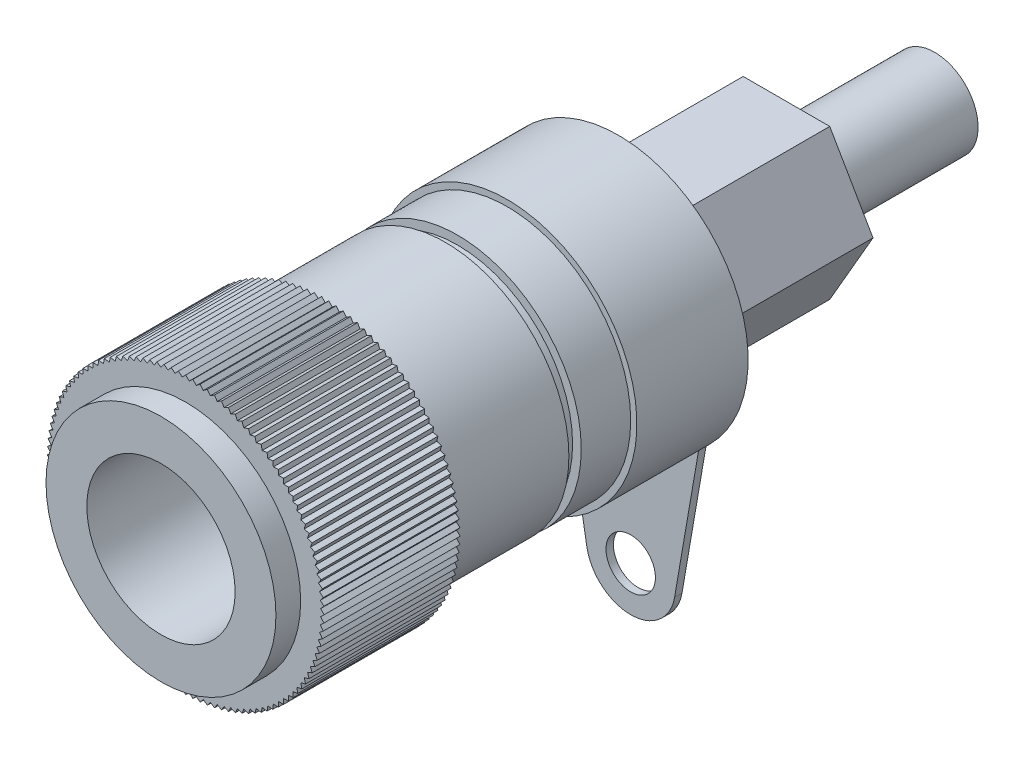
SolidWorks part; units mm, degrees
ref_plane "Alzado" through (0, 0, 0) normal (0, 0, 1) x (1, 0, 0)
ref_plane "Planta" through (0, 0, 0) normal (0, 1, 0) x (1, 0, 0)
ref_plane "Vista lateral" through (0, 0, 0) normal (1, 0, 0) x (0, 0, -1)
sketch "Croquis2" plane through (0, 0, 0) normal (0, 0, 1) x (1, 0, 0)
  circle A0 centre (0, 0) radius 3
  circle A1 centre (0, 0) radius 4.65
  dimension "D1" = 6
  dimension "D2" = 9.3
extrude "Saliente-Extruir1" add sketch "Croquis2" against normal blind 1
sketch "Croquis3" plane through (0, 0, -1) normal (0, 0, -1) x (-1, 0, 0)
  line L0 (0, 0) -> (0, 5.6) construction
  line L1 (0.1429, 5.4571) -> (0, 5.6)
  line L2 (0, 5.6) -> (-0.1429, 5.4571)
  line L3 (0.2931, 5.5923) -> (0.1429, 5.4571)
  line L4 (0.4283, 5.4421) -> (0.2931, 5.5923)
  line L5 (0.5854, 5.5693) -> (0.4283, 5.4421)
  line L6 (0.7125, 5.4123) -> (0.5854, 5.5693)
  line L7 (0.876, 5.5311) -> (0.7125, 5.4123)
  line L8 (0.9948, 5.3676) -> (0.876, 5.5311)
  line L9 (1.1643, 5.4776) -> (0.9948, 5.3676)
  line L10 (1.2744, 5.3081) -> (1.1643, 5.4776)
  line L11 (1.4494, 5.4092) -> (1.2744, 5.3081)
  line L12 (1.5504, 5.2342) -> (1.4494, 5.4092)
  line L13 (1.7305, 5.3259) -> (1.5504, 5.2342)
  line L14 (1.8222, 5.1459) -> (1.7305, 5.3259)
  line L15 (2.0069, 5.2281) -> (1.8222, 5.1459)
  line L16 (2.0891, 5.0434) -> (2.0069, 5.2281)
  line L17 (2.2777, 5.1159) -> (2.0891, 5.0434)
  line L18 (2.3501, 4.9272) -> (2.2777, 5.1159)
  line L19 (2.5423, 4.9896) -> (2.3501, 4.9272)
  line L20 (2.6048, 4.7974) -> (2.5423, 4.9896)
  line L21 (2.8, 4.8497) -> (2.6048, 4.7974)
  line L22 (2.8523, 4.6545) -> (2.8, 4.8497)
  line L23 (3.05, 4.6966) -> (2.8523, 4.6545)
  line L24 (3.092, 4.4989) -> (3.05, 4.6966)
  line L25 (3.2916, 4.5305) -> (3.092, 4.4989)
  line L26 (3.3232, 4.3309) -> (3.2916, 4.5305)
  line L27 (3.5242, 4.352) -> (3.3232, 4.3309)
  line L28 (3.5453, 4.151) -> (3.5242, 4.352)
  line L29 (3.7471, 4.1616) -> (3.5453, 4.151)
  line L30 (3.7577, 3.9598) -> (3.7471, 4.1616)
  line L31 (3.9598, 3.9598) -> (3.7577, 3.9598)
  line L32 (3.9598, 3.7577) -> (3.9598, 3.9598)
  line L33 (4.1616, 3.7471) -> (3.9598, 3.7577)
  line L34 (4.151, 3.5453) -> (4.1616, 3.7471)
  line L35 (4.352, 3.5242) -> (4.151, 3.5453)
  line L36 (4.3309, 3.3232) -> (4.352, 3.5242)
  line L37 (4.5305, 3.2916) -> (4.3309, 3.3232)
  line L38 (4.4989, 3.092) -> (4.5305, 3.2916)
  line L39 (4.6966, 3.05) -> (4.4989, 3.092)
  line L40 (4.6545, 2.8523) -> (4.6966, 3.05)
  line L41 (4.8497, 2.8) -> (4.6545, 2.8523)
  line L42 (4.7974, 2.6048) -> (4.8497, 2.8)
  line L43 (4.9896, 2.5423) -> (4.7974, 2.6048)
  line L44 (4.9272, 2.3501) -> (4.9896, 2.5423)
  line L45 (5.1159, 2.2777) -> (4.9272, 2.3501)
  line L46 (5.0434, 2.0891) -> (5.1159, 2.2777)
  line L47 (5.2281, 2.0069) -> (5.0434, 2.0891)
  line L48 (5.1459, 1.8222) -> (5.2281, 2.0069)
  line L49 (5.3259, 1.7305) -> (5.1459, 1.8222)
  line L50 (5.2342, 1.5504) -> (5.3259, 1.7305)
  line L51 (5.4092, 1.4494) -> (5.2342, 1.5504)
  line L52 (5.3081, 1.2744) -> (5.4092, 1.4494)
  line L53 (5.4776, 1.1643) -> (5.3081, 1.2744)
  line L54 (5.3676, 0.9948) -> (5.4776, 1.1643)
  line L55 (5.5311, 0.876) -> (5.3676, 0.9948)
  line L56 (5.4123, 0.7125) -> (5.5311, 0.876)
  line L57 (5.5693, 0.5854) -> (5.4123, 0.7125)
  line L58 (5.4421, 0.4283) -> (5.5693, 0.5854)
  line L59 (5.5923, 0.2931) -> (5.4421, 0.4283)
  line L60 (5.4571, 0.1429) -> (5.5923, 0.2931)
  line L61 (5.6, 0) -> (5.4571, 0.1429)
  line L62 (5.4571, -0.1429) -> (5.6, 0)
  line L63 (5.5923, -0.2931) -> (5.4571, -0.1429)
  line L64 (5.4421, -0.4283) -> (5.5923, -0.2931)
  line L65 (5.5693, -0.5854) -> (5.4421, -0.4283)
  line L66 (5.4123, -0.7125) -> (5.5693, -0.5854)
  line L67 (5.5311, -0.876) -> (5.4123, -0.7125)
  line L68 (5.3676, -0.9948) -> (5.5311, -0.876)
  line L69 (5.4776, -1.1643) -> (5.3676, -0.9948)
  line L70 (5.3081, -1.2744) -> (5.4776, -1.1643)
  line L71 (5.4092, -1.4494) -> (5.3081, -1.2744)
  line L72 (5.2342, -1.5504) -> (5.4092, -1.4494)
  line L73 (5.3259, -1.7305) -> (5.2342, -1.5504)
  line L74 (5.1459, -1.8222) -> (5.3259, -1.7305)
  line L75 (5.2281, -2.0069) -> (5.1459, -1.8222)
  line L76 (5.0434, -2.0891) -> (5.2281, -2.0069)
  line L77 (5.1159, -2.2777) -> (5.0434, -2.0891)
  line L78 (4.9272, -2.3501) -> (5.1159, -2.2777)
  line L79 (4.9896, -2.5423) -> (4.9272, -2.3501)
  line L80 (4.7974, -2.6048) -> (4.9896, -2.5423)
  line L81 (4.8497, -2.8) -> (4.7974, -2.6048)
  line L82 (4.6545, -2.8523) -> (4.8497, -2.8)
  line L83 (4.6966, -3.05) -> (4.6545, -2.8523)
  line L84 (4.4989, -3.092) -> (4.6966, -3.05)
  line L85 (4.5305, -3.2916) -> (4.4989, -3.092)
  line L86 (4.3309, -3.3232) -> (4.5305, -3.2916)
  line L87 (4.352, -3.5242) -> (4.3309, -3.3232)
  line L88 (4.151, -3.5453) -> (4.352, -3.5242)
  line L89 (4.1616, -3.7471) -> (4.151, -3.5453)
  line L90 (3.9598, -3.7577) -> (4.1616, -3.7471)
  line L91 (3.9598, -3.9598) -> (3.9598, -3.7577)
  line L92 (3.7577, -3.9598) -> (3.9598, -3.9598)
  line L93 (3.7471, -4.1616) -> (3.7577, -3.9598)
  line L94 (3.5453, -4.151) -> (3.7471, -4.1616)
  line L95 (3.5242, -4.352) -> (3.5453, -4.151)
  line L96 (3.3232, -4.3309) -> (3.5242, -4.352)
  line L97 (3.2916, -4.5305) -> (3.3232, -4.3309)
  line L98 (3.092, -4.4989) -> (3.2916, -4.5305)
  line L99 (3.05, -4.6966) -> (3.092, -4.4989)
  line L100 (2.8523, -4.6545) -> (3.05, -4.6966)
  line L101 (2.8, -4.8497) -> (2.8523, -4.6545)
  line L102 (2.6048, -4.7974) -> (2.8, -4.8497)
  line L103 (2.5423, -4.9896) -> (2.6048, -4.7974)
  line L104 (2.3501, -4.9272) -> (2.5423, -4.9896)
  line L105 (2.2777, -5.1159) -> (2.3501, -4.9272)
  line L106 (2.0891, -5.0434) -> (2.2777, -5.1159)
  line L107 (2.0069, -5.2281) -> (2.0891, -5.0434)
  line L108 (1.8222, -5.1459) -> (2.0069, -5.2281)
  line L109 (1.7305, -5.3259) -> (1.8222, -5.1459)
  line L110 (1.5504, -5.2342) -> (1.7305, -5.3259)
  line L111 (1.4494, -5.4092) -> (1.5504, -5.2342)
  line L112 (1.2744, -5.3081) -> (1.4494, -5.4092)
  line L113 (1.1643, -5.4776) -> (1.2744, -5.3081)
  line L114 (0.9948, -5.3676) -> (1.1643, -5.4776)
  line L115 (0.876, -5.5311) -> (0.9948, -5.3676)
  line L116 (0.7125, -5.4123) -> (0.876, -5.5311)
  line L117 (0.5854, -5.5693) -> (0.7125, -5.4123)
  line L118 (0.4283, -5.4421) -> (0.5854, -5.5693)
  line L119 (0.2931, -5.5923) -> (0.4283, -5.4421)
  line L120 (0.1429, -5.4571) -> (0.2931, -5.5923)
  line L121 (0, -5.6) -> (0.1429, -5.4571)
  line L122 (-0.1429, -5.4571) -> (0, -5.6)
  line L123 (-0.2931, -5.5923) -> (-0.1429, -5.4571)
  line L124 (-0.4283, -5.4421) -> (-0.2931, -5.5923)
  line L125 (-0.5854, -5.5693) -> (-0.4283, -5.4421)
  line L126 (-0.7125, -5.4123) -> (-0.5854, -5.5693)
  line L127 (-0.876, -5.5311) -> (-0.7125, -5.4123)
  line L128 (-0.9948, -5.3676) -> (-0.876, -5.5311)
  line L129 (-1.1643, -5.4776) -> (-0.9948, -5.3676)
  line L130 (-1.2744, -5.3081) -> (-1.1643, -5.4776)
  line L131 (-1.4494, -5.4092) -> (-1.2744, -5.3081)
  line L132 (-1.5504, -5.2342) -> (-1.4494, -5.4092)
  line L133 (-1.7305, -5.3259) -> (-1.5504, -5.2342)
  line L134 (-1.8222, -5.1459) -> (-1.7305, -5.3259)
  line L135 (-2.0069, -5.2281) -> (-1.8222, -5.1459)
  line L136 (-2.0891, -5.0434) -> (-2.0069, -5.2281)
  line L137 (-2.2777, -5.1159) -> (-2.0891, -5.0434)
  line L138 (-2.3501, -4.9272) -> (-2.2777, -5.1159)
  line L139 (-2.5423, -4.9896) -> (-2.3501, -4.9272)
  line L140 (-2.6048, -4.7974) -> (-2.5423, -4.9896)
  line L141 (-2.8, -4.8497) -> (-2.6048, -4.7974)
  line L142 (-2.8523, -4.6545) -> (-2.8, -4.8497)
  line L143 (-3.05, -4.6966) -> (-2.8523, -4.6545)
  line L144 (-3.092, -4.4989) -> (-3.05, -4.6966)
  line L145 (-3.2916, -4.5305) -> (-3.092, -4.4989)
  line L146 (-3.3232, -4.3309) -> (-3.2916, -4.5305)
  line L147 (-3.5242, -4.352) -> (-3.3232, -4.3309)
  line L148 (-3.5453, -4.151) -> (-3.5242, -4.352)
  line L149 (-3.7471, -4.1616) -> (-3.5453, -4.151)
  line L150 (-3.7577, -3.9598) -> (-3.7471, -4.1616)
  line L151 (-3.9598, -3.9598) -> (-3.7577, -3.9598)
  line L152 (-3.9598, -3.7577) -> (-3.9598, -3.9598)
  line L153 (-4.1616, -3.7471) -> (-3.9598, -3.7577)
  line L154 (-4.151, -3.5453) -> (-4.1616, -3.7471)
  line L155 (-4.352, -3.5242) -> (-4.151, -3.5453)
  line L156 (-4.3309, -3.3232) -> (-4.352, -3.5242)
  line L157 (-4.5305, -3.2916) -> (-4.3309, -3.3232)
  line L158 (-4.4989, -3.092) -> (-4.5305, -3.2916)
  line L159 (-4.6966, -3.05) -> (-4.4989, -3.092)
  line L160 (-4.6545, -2.8523) -> (-4.6966, -3.05)
  line L161 (-4.8497, -2.8) -> (-4.6545, -2.8523)
  line L162 (-4.7974, -2.6048) -> (-4.8497, -2.8)
  line L163 (-4.9896, -2.5423) -> (-4.7974, -2.6048)
  line L164 (-4.9272, -2.3501) -> (-4.9896, -2.5423)
  line L165 (-5.1159, -2.2777) -> (-4.9272, -2.3501)
  line L166 (-5.0434, -2.0891) -> (-5.1159, -2.2777)
  line L167 (-5.2281, -2.0069) -> (-5.0434, -2.0891)
  line L168 (-5.1459, -1.8222) -> (-5.2281, -2.0069)
  line L169 (-5.3259, -1.7305) -> (-5.1459, -1.8222)
  line L170 (-5.2342, -1.5504) -> (-5.3259, -1.7305)
  line L171 (-5.4092, -1.4494) -> (-5.2342, -1.5504)
  line L172 (-5.3081, -1.2744) -> (-5.4092, -1.4494)
  line L173 (-5.4776, -1.1643) -> (-5.3081, -1.2744)
  line L174 (-5.3676, -0.9948) -> (-5.4776, -1.1643)
  line L175 (-5.5311, -0.876) -> (-5.3676, -0.9948)
  line L176 (-5.4123, -0.7125) -> (-5.5311, -0.876)
  line L177 (-5.5693, -0.5854) -> (-5.4123, -0.7125)
  line L178 (-5.4421, -0.4283) -> (-5.5693, -0.5854)
  line L179 (-5.5923, -0.2931) -> (-5.4421, -0.4283)
  line L180 (-5.4571, -0.1429) -> (-5.5923, -0.2931)
  line L181 (-5.6, 0) -> (-5.4571, -0.1429)
  line L182 (-5.4571, 0.1429) -> (-5.6, 0)
  line L183 (-5.5923, 0.2931) -> (-5.4571, 0.1429)
  line L184 (-5.4421, 0.4283) -> (-5.5923, 0.2931)
  line L185 (-5.5693, 0.5854) -> (-5.4421, 0.4283)
  line L186 (-5.4123, 0.7125) -> (-5.5693, 0.5854)
  line L187 (-5.5311, 0.876) -> (-5.4123, 0.7125)
  line L188 (-5.3676, 0.9948) -> (-5.5311, 0.876)
  line L189 (-5.4776, 1.1643) -> (-5.3676, 0.9948)
  line L190 (-5.3081, 1.2744) -> (-5.4776, 1.1643)
  line L191 (-5.4092, 1.4494) -> (-5.3081, 1.2744)
  line L192 (-5.2342, 1.5504) -> (-5.4092, 1.4494)
  line L193 (-5.3259, 1.7305) -> (-5.2342, 1.5504)
  line L194 (-5.1459, 1.8222) -> (-5.3259, 1.7305)
  line L195 (-5.2281, 2.0069) -> (-5.1459, 1.8222)
  line L196 (-5.0434, 2.0891) -> (-5.2281, 2.0069)
  line L197 (-5.1159, 2.2777) -> (-5.0434, 2.0891)
  line L198 (-4.9272, 2.3501) -> (-5.1159, 2.2777)
  line L199 (-4.9896, 2.5423) -> (-4.9272, 2.3501)
  line L200 (-4.7974, 2.6048) -> (-4.9896, 2.5423)
  line L201 (-4.8497, 2.8) -> (-4.7974, 2.6048)
  line L202 (-4.6545, 2.8523) -> (-4.8497, 2.8)
  line L203 (-4.6966, 3.05) -> (-4.6545, 2.8523)
  line L204 (-4.4989, 3.092) -> (-4.6966, 3.05)
  line L205 (-4.5305, 3.2916) -> (-4.4989, 3.092)
  line L206 (-4.3309, 3.3232) -> (-4.5305, 3.2916)
  line L207 (-4.352, 3.5242) -> (-4.3309, 3.3232)
  line L208 (-4.151, 3.5453) -> (-4.352, 3.5242)
  line L209 (-4.1616, 3.7471) -> (-4.151, 3.5453)
  line L210 (-3.9598, 3.7577) -> (-4.1616, 3.7471)
  line L211 (-3.9598, 3.9598) -> (-3.9598, 3.7577)
  line L212 (-3.7577, 3.9598) -> (-3.9598, 3.9598)
  line L213 (-3.7471, 4.1616) -> (-3.7577, 3.9598)
  line L214 (-3.5453, 4.151) -> (-3.7471, 4.1616)
  line L215 (-3.5242, 4.352) -> (-3.5453, 4.151)
  line L216 (-3.3232, 4.3309) -> (-3.5242, 4.352)
  line L217 (-3.2916, 4.5305) -> (-3.3232, 4.3309)
  line L218 (-3.092, 4.4989) -> (-3.2916, 4.5305)
  line L219 (-3.05, 4.6966) -> (-3.092, 4.4989)
  line L220 (-2.8523, 4.6545) -> (-3.05, 4.6966)
  line L221 (-2.8, 4.8497) -> (-2.8523, 4.6545)
  line L222 (-2.6048, 4.7974) -> (-2.8, 4.8497)
  line L223 (-2.5423, 4.9896) -> (-2.6048, 4.7974)
  line L224 (-2.3501, 4.9272) -> (-2.5423, 4.9896)
  line L225 (-2.2777, 5.1159) -> (-2.3501, 4.9272)
  line L226 (-2.0891, 5.0434) -> (-2.2777, 5.1159)
  line L227 (-2.0069, 5.2281) -> (-2.0891, 5.0434)
  line L228 (-1.8222, 5.1459) -> (-2.0069, 5.2281)
  line L229 (-1.7305, 5.3259) -> (-1.8222, 5.1459)
  line L230 (-1.5504, 5.2342) -> (-1.7305, 5.3259)
  line L231 (-1.4494, 5.4092) -> (-1.5504, 5.2342)
  line L232 (-1.2744, 5.3081) -> (-1.4494, 5.4092)
  line L233 (-1.1643, 5.4776) -> (-1.2744, 5.3081)
  line L234 (-0.9948, 5.3676) -> (-1.1643, 5.4776)
  line L235 (-0.876, 5.5311) -> (-0.9948, 5.3676)
  line L236 (-0.7125, 5.4123) -> (-0.876, 5.5311)
  line L237 (-0.5854, 5.5693) -> (-0.7125, 5.4123)
  line L238 (-0.4283, 5.4421) -> (-0.5854, 5.5693)
  line L239 (-0.2931, 5.5923) -> (-0.4283, 5.4421)
  line L240 (-0.1429, 5.4571) -> (-0.2931, 5.5923)
  circle A0 centre (0, 0) radius 3 construction
  circle A1 centre (0, 0) radius 3
  circle A2 centre (0, 0) radius 5.6 construction
  circle A3 centre (0, 0) radius 4.65 construction
  point P8 (0.1429, 5.4571)
  point P11 (-0.1429, 5.4571)
  point P367 (0, 0)
  dimension "D1" = 11.2
  dimension "D3" = 120
extrude "Saliente-Extruir2" add sketch "Croquis3" along normal blind 5.5
sketch "Croquis4" plane through (0, 0, -6.5) normal (0, 0, -1) x (-1, 0, 0)
  circle A0 centre (0, 0) radius 1.75
  circle A1 centre (0, 0) radius 5
  dimension "D1" = 3.5
  dimension "D2" = 10
extrude "Saliente-Extruir3" add sketch "Croquis4" along normal blind 5
sketch "Croquis5" plane through (0, 0, -11.5) normal (0, 0, -1) x (-1, 0, 0)
  circle A0 centre (0, 0) radius 4.65 construction
  circle A1 centre (0, 0) radius 1.75 construction
  circle A2 centre (0, 0) radius 4.65
  circle A3 centre (0, 0) radius 1.75
extrude "Saliente-Extruir4" add sketch "Croquis5" along normal blind 0.5
sketch "Croquis6" plane through (0, 0, -12) normal (0, 0, -1) x (-1, 0, 0)
  circle A0 centre (0, 0) radius 5 construction
  circle A1 centre (0, 0) radius 1.75 construction
  circle A2 centre (0, 0) radius 5
  circle A3 centre (0, 0) radius 1.75
extrude "Saliente-Extruir5" add sketch "Croquis6" along normal blind 2
sketch "Croquis7" plane through (0, 0, -14) normal (0, 0, -1) x (-1, 0, 0)
  circle A0 centre (0, 0) radius 1.75 construction
  circle A1 centre (0, 0) radius 1.75
  circle A2 centre (0, 0) radius 5.25
  dimension "D1" = 10.5
extrude "Saliente-Extruir6" add sketch "Croquis7" along normal blind 4.5
sketch "Croquis8" plane through (0, 0, -18.5) normal (0, 0, -1) x (-1, 0, 0)
  circle A0 centre (0, 0) radius 4.5
  dimension "D1" = 9
extrude "Saliente-Extruir7" add sketch "Croquis8" along normal blind 0.5
sketch "Croquis9" plane through (0, 0, -19) normal (0, 0, -1) x (-1, 0, 0)
  line L0 (-3.4491, -0.595) -> (-1.7738, -10.306)
  line L1 (0, 0) -> (0, -10) construction
  line L2 (3.4491, -0.595) -> (1.7738, -10.306)
  arc A0 (3.4491, -0.595) -> (-3.4491, -0.595) centre (0, 0) ccw
  circle A1 centre (0, -10) radius 1
  arc A2 (-1.7738, -10.306) -> (1.7738, -10.306) centre (0, -10) ccw
  circle A3 centre (0, -10) radius 1.8 construction
  dimension "D1" = 7
  dimension "D3" = 2
  dimension "D2" = 10
  dimension "D4" = 0.8
extrude "Saliente-Extruir8" add sketch "Croquis9" along normal blind 0.3
sketch "Croquis10" plane through (0, 0, -19.3) normal (0, 0, -1) x (-1, 0, 0)
  line L1 (1.75, -3.0311) -> (3.5, 0)
  line L2 (3.5, 0) -> (1.75, 3.0311)
  line L3 (1.75, 3.0311) -> (-1.75, 3.0311)
  line L4 (-1.75, 3.0311) -> (-3.5, 0)
  line L5 (-3.5, 0) -> (-1.75, -3.0311)
  line L6 (-1.75, -3.0311) -> (1.75, -3.0311)
  circle A0 centre (0, 0) radius 3.0311 construction
  dimension "D1" = 3.5
extrude "Saliente-Extruir9" add sketch "Croquis10" along normal blind 6
sketch "Croquis11" plane through (0, 0, -25.3) normal (0, 0, -1) x (-1, 0, 0)
  circle A0 centre (0, 0) radius 1.75
  dimension "D1" = 3.5
extrude "Saliente-Extruir10" add sketch "Croquis11" along normal blind 6
